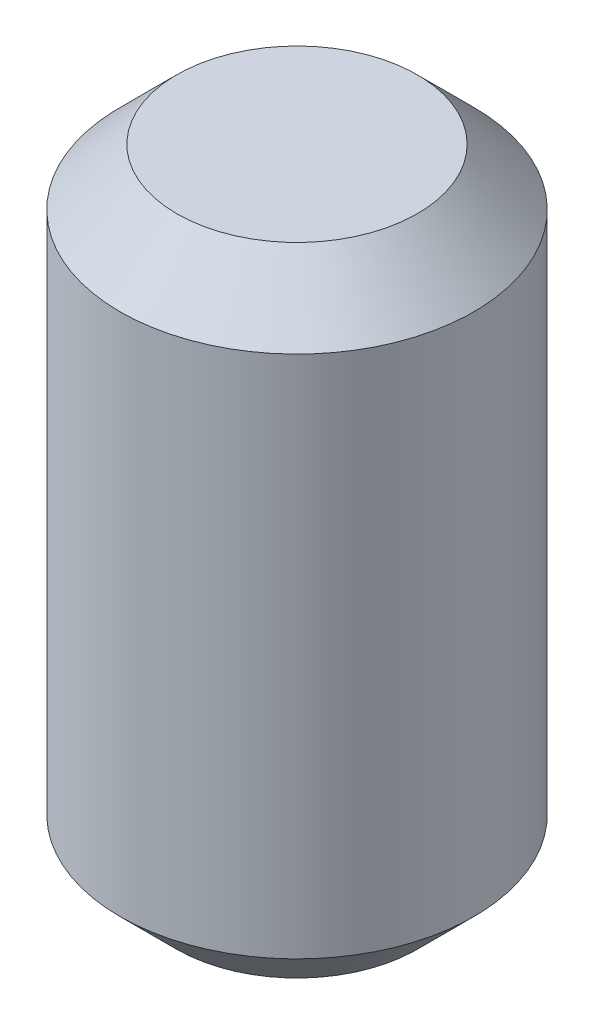
SolidWorks part; units mm, degrees
ref_plane "Front Plane" through (0, 0, 0) normal (0, 0, 1) x (1, 0, 0)
ref_plane "Top Plane" through (0, 0, 0) normal (0, 1, 0) x (1, 0, 0)
ref_plane "Right Plane" through (0, 0, 0) normal (1, 0, 0) x (0, 0, -1)
sketch "Sketch1" plane through (0, 0, 0) normal (0, 1, 0) x (1, 0, 0)
  circle A0 centre (0, 0) radius 2.5
  dimension "D1" = 5
extrude "Boss-Extrude1" add sketch "Sketch1" along normal blind 9
chamfer "Chamfer1" distance 0.8 angle 45 2 edges at (0, 0, 2.5) (0, 9, 2.5)
